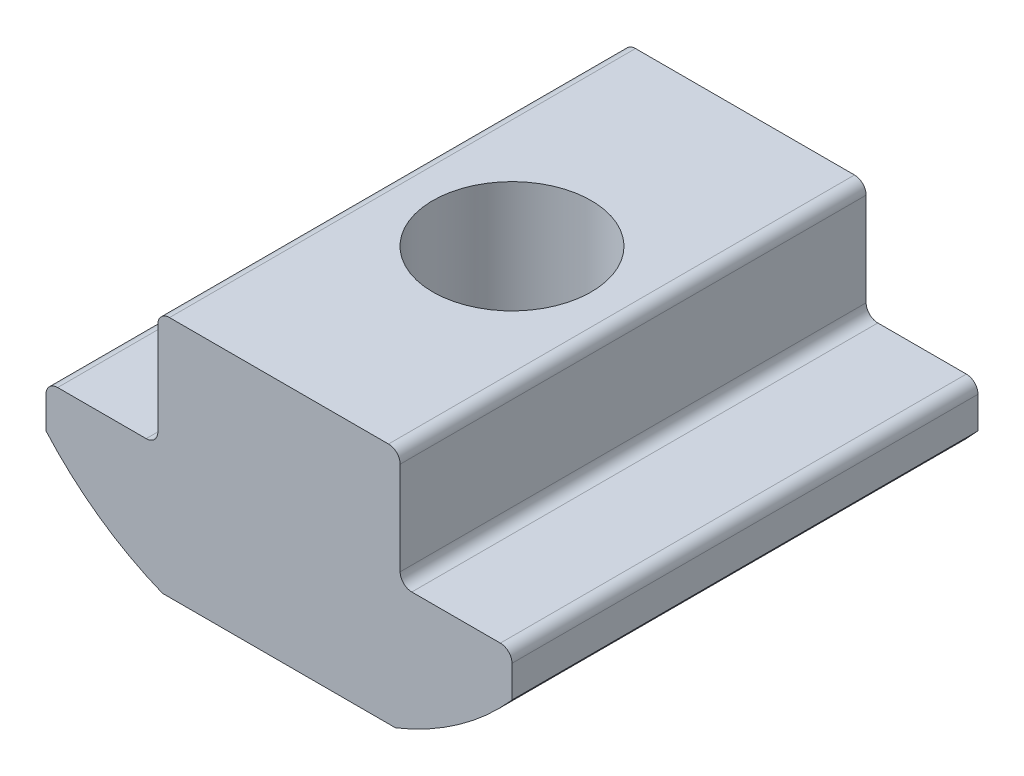
SolidWorks part; units mm, degrees
ref_plane "前视基准面" through (0, 0, 0) normal (0, 0, 1) x (1, 0, 0)
ref_plane "上视基准面" through (0, 0, 0) normal (0, 1, 0) x (1, 0, 0)
ref_plane "右视基准面" through (0, 0, 0) normal (1, 0, 0) x (0, 0, -1)
sketch "草图1" plane through (0, 0, 0) normal (0, 0, 1) x (1, 0, 0)
  line B0 (-5, 0) -> (5, 0)
  line B1 (10, 4.9) -> (10, 3.5369)
  line B2 (-10, 4.9) -> (-10, 3.5369)
  line B3 (-4.7, 10.4) -> (4.7, 10.4)
  line B4 (-9.5, 5.4) -> (-5.7, 5.4)
  line B5 (5.7, 5.4) -> (9.5, 5.4)
  line B6 (-5.2, 9.9) -> (-5.2, 5.9)
  line B7 (5.2, 9.9) -> (5.2, 5.9)
  arc B8 (5.2, 5.9) -> (5.7, 5.4) centre (5.7, 5.9) ccw
  arc B9 (-5.7, 5.4) -> (-5.2, 5.9) centre (-5.7, 5.9) ccw
  arc B10 (-4.7, 10.4) -> (-5.2, 9.9) centre (-4.7, 9.9) ccw
  arc B11 (5.2, 9.9) -> (4.7, 10.4) centre (4.7, 9.9) ccw
  arc B12 (-9.5, 5.4) -> (-10, 4.9) centre (-9.5, 4.9) ccw
  arc B13 (10, 4.9) -> (9.5, 5.4) centre (9.5, 4.9) ccw
  arc B14 (-10, 3.5369) -> (-5, 0) centre (-0.0581, 12.289) ccw
  arc B15 (5, 0) -> (10, 3.5369) centre (0.0581, 12.289) ccw
sketch_block_instance "A$C0A225C0E-1"
sketch_block "A$C0A225C0E"
extrude "凸台-拉伸1" add sketch "草图1" along normal mid plane 20
sketch "草图3" plane through (0, 10.4, 0) normal (0, 1, 0) x (1, 0, 0)
  point P0 (0, 0)
hole_wizard "M8 螺纹孔1" positions "3D草图2" profile "草图5" tap size "M8" standard "Iso"
sketch3d "3D草图2"
  point P0 (0, 10.4, 0)
sketch "草图5" plane through (0, 10.4, 0) normal (1, 0, 0) x (0, 0, 1)
  line L0 (0, 0) -> (0, 21.7929)
  line L1 (0, 21.7929) -> (3.4, 19.75)
  line L2 (3.4, 19.75) -> (3.4, 0)
  line L5 (3.4, 0) -> (0, 0)
  line L10 (0, 21.7929) -> (-3.4, 19.75) construction
  line L11 (0, -6.35) -> (0, 107.95) construction
  dimension "螺纹孔钻头直径" = 6.8
  dimension "螺纹孔钻头深度" = 19.75
  dimension "导头角度" = 118
cosmetic thread "孔螺蚊线1"
